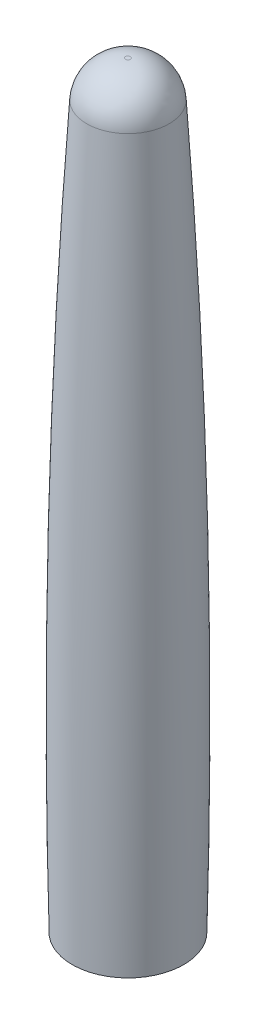
SolidWorks part; units mm, degrees
ref_plane "Front Plane" through (0, 0, 0) normal (0, 0, 1) x (1, 0, 0)
ref_plane "Top Plane" through (0, 0, 0) normal (0, 1, 0) x (1, 0, 0)
ref_plane "Right Plane" through (0, 0, 0) normal (1, 0, 0) x (0, 0, -1)
sketch "Sketch1" plane through (0, 0, 0) normal (0, 0, 1) x (1, 0, 0)
  line L0 (0, 39) -> (0, -39) construction
  line L1 (-4.2444, 35.2516) -> (-5.75, -39) construction
  line L2 (0, 39) -> (-0.2523, 39)
  line L3 (0, 38) -> (-0.2523, 38)
  line L4 (0, 39) -> (0, 38)
  line L5 (-3.245, 35.2085) -> (-4.7502, -39.0203) construction
  line L6 (-5.75, -39) -> (-4.75, -39)
  arc A0 (-0.2523, 39) -> (-4.2444, 35.2516) centre (-0.2523, 35) ccw
  arc A1 (-0.2523, 38) -> (-3.245, 35.2085) centre (-0.2523, 35) ccw
  spline S0 degree 3 poles (-4.2444, 35.2516) (-4.9846, 23.5067) (-6.0412, -1.2325) (-6.0413, -25.9944) (-5.75, -39) knots 0.048102 0.048102 0.048102 0.048102 0.500241 1 1 1 1
  spline S1 degree 2 poles (-3.245, 35.2085) (-5.5828, -1.8619) (-4.75, -39) knots 0 0 0 1 1 1
  point P3 (0, 0)
  dimension "D3" = 4
  dimension "D1" = 78
  dimension "D2" = 5.75
  dimension "D6" = 1
  dimension "D7" = 1
  dimension "D4" = 1
  dimension "D5" = 1
revolve "Revolve2" add sketch "Sketch1" angle 360 about L0
